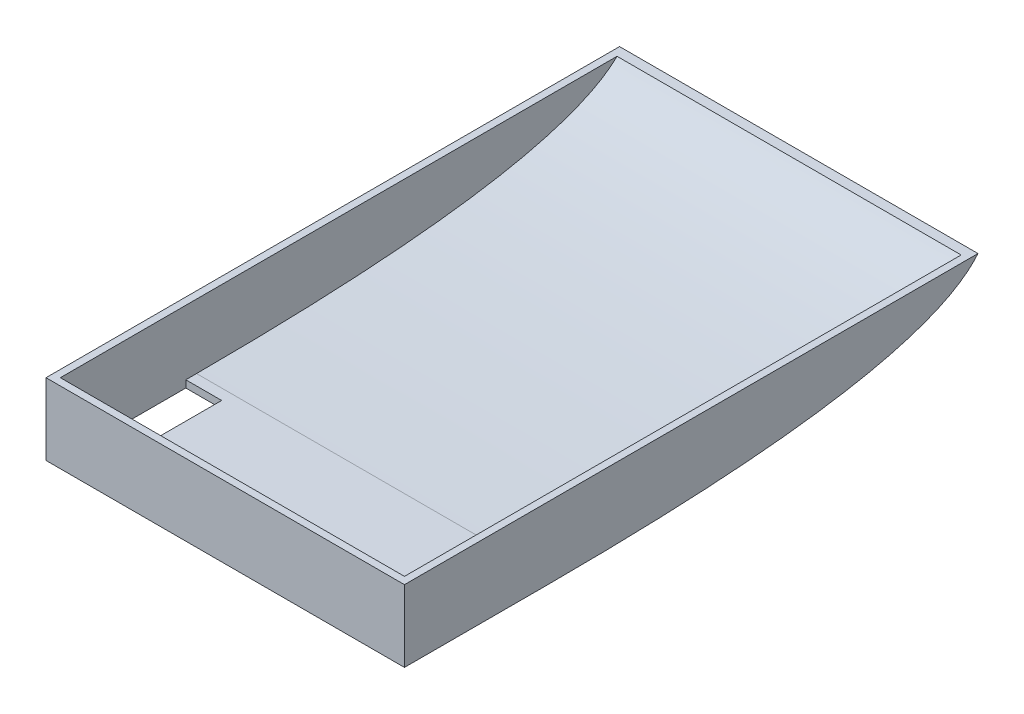
SolidWorks part; units mm, degrees
ref_plane "Front Plane" through (0, 0, 0) normal (0, 0, 1) x (1, 0, 0)
ref_plane "Top Plane" through (0, 0, 0) normal (0, 1, 0) x (1, 0, 0)
ref_plane "Right Plane" through (0, 0, 0) normal (1, 0, 0) x (0, 0, -1)
sketch "Sketch1" plane through (0, 0, 0) normal (1, 0, 0) x (0, 0, -1)
  line L0 (-50.8, 25.4) -> (-50.8, 0)
  line L1 (-50.8, 0) -> (0, 0)
  line L2 (-50.8, 25.4) -> (152.4, 25.4)
  line L3 (0, 0) -> (90.3999, 0.1285) construction
  line L4 (90.3999, 0.1285) -> (138.8723, 8.8623) construction
  line L5 (138.8723, 8.8623) -> (152.4, 25.4) construction
  spline S0 degree 3 poles (0, 0) (90.3999, 0.1285) (138.8723, 8.8623) (152.4, 25.4) knots 0 0 0 0 1 1 1 1
  dimension "D1" = 25.4
  dimension "D2" = 203.2
  dimension "D3" = 50.8
extrude "Boss-Extrude1" add sketch "Sketch1" along normal mid plane 127
shell "Shell1" thickness 2.54
sketch "Sketch4" plane through (0, 25.4, 0) normal (0, 1, 0) x (1, 0, 0)
  line L1 (-60.96, -48.26) -> (-48.26, -48.26)
  line L2 (-60.96, -48.26) -> (-60.96, -3.81)
  line L3 (-60.96, -3.81) -> (-48.26, -3.81)
  line L4 (-48.26, -48.26) -> (-48.26, -3.81)
  line L5 (60.96, -48.26) -> (48.26, -48.26)
  line L6 (60.96, -48.26) -> (60.96, -3.81)
  line L7 (60.96, -3.81) -> (48.26, -3.81)
  line L8 (48.26, -48.26) -> (48.26, -3.81)
  dimension "D1" = 44.45
  dimension "D2" = 12.7
extrude "Cut-Extrude1" cut sketch "Sketch4" against normal through all
